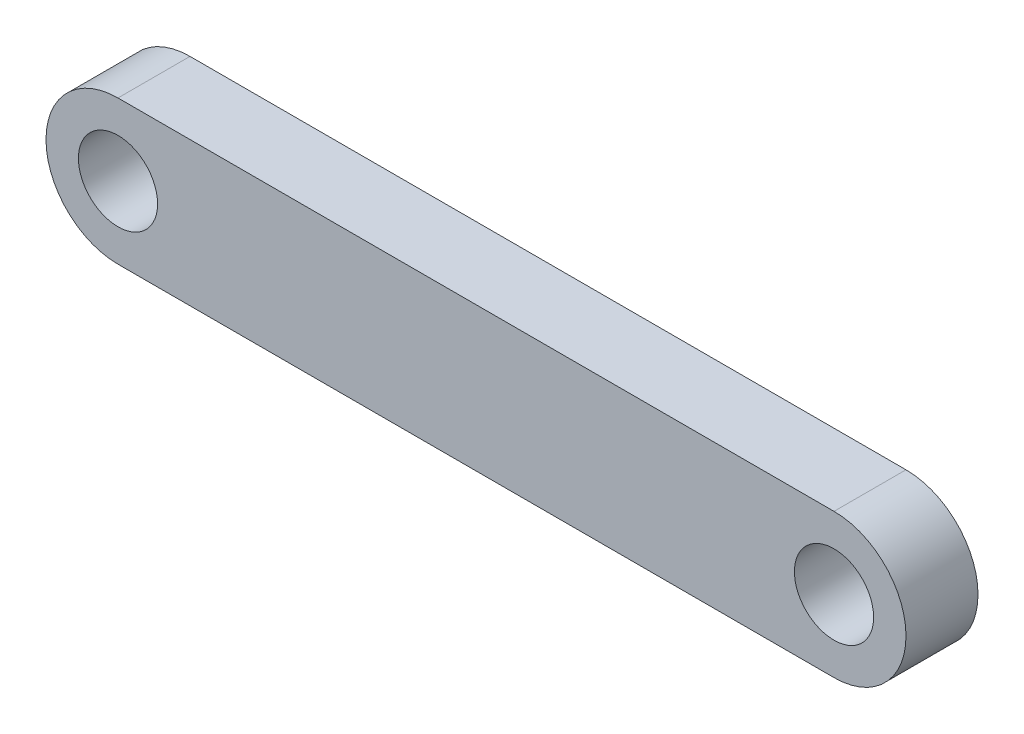
SolidWorks part; units mm, degrees
ref_plane "Front Plane" through (0, 0, 0) normal (0, 0, 1) x (1, 0, 0)
ref_plane "Top Plane" through (0, 0, 0) normal (0, 1, 0) x (1, 0, 0)
ref_plane "Right Plane" through (0, 0, 0) normal (1, 0, 0) x (0, 0, -1)
sketch "Sketch1" plane through (0, 0, 0) normal (0, 0, 1) x (1, 0, 0)
  line L0 (-14.9171, 3.0494) -> (14.9171, 3.0494)
  line L1 (14.9171, -2.9506) -> (-14.9171, -2.9506)
  line L2 (-14.9171, 0.0494) -> (14.9171, 0.0494) construction
  arc A0 (14.9171, -2.9506) -> (14.9171, 3.0494) centre (14.9171, 0.0494) ccw
  arc A1 (-14.9171, 3.0494) -> (-14.9171, -2.9506) centre (-14.9171, 0.0494) ccw
  circle A2 centre (-14.9171, 0.0494) radius 1.65
  circle A3 centre (14.9171, 0.0494) radius 1.65
  point P9 (0, 0.0494)
  dimension "D1" = 6
  dimension "D2" = 3.3
extrude "Boss-Extrude1" add sketch "Sketch1" along normal blind 3
